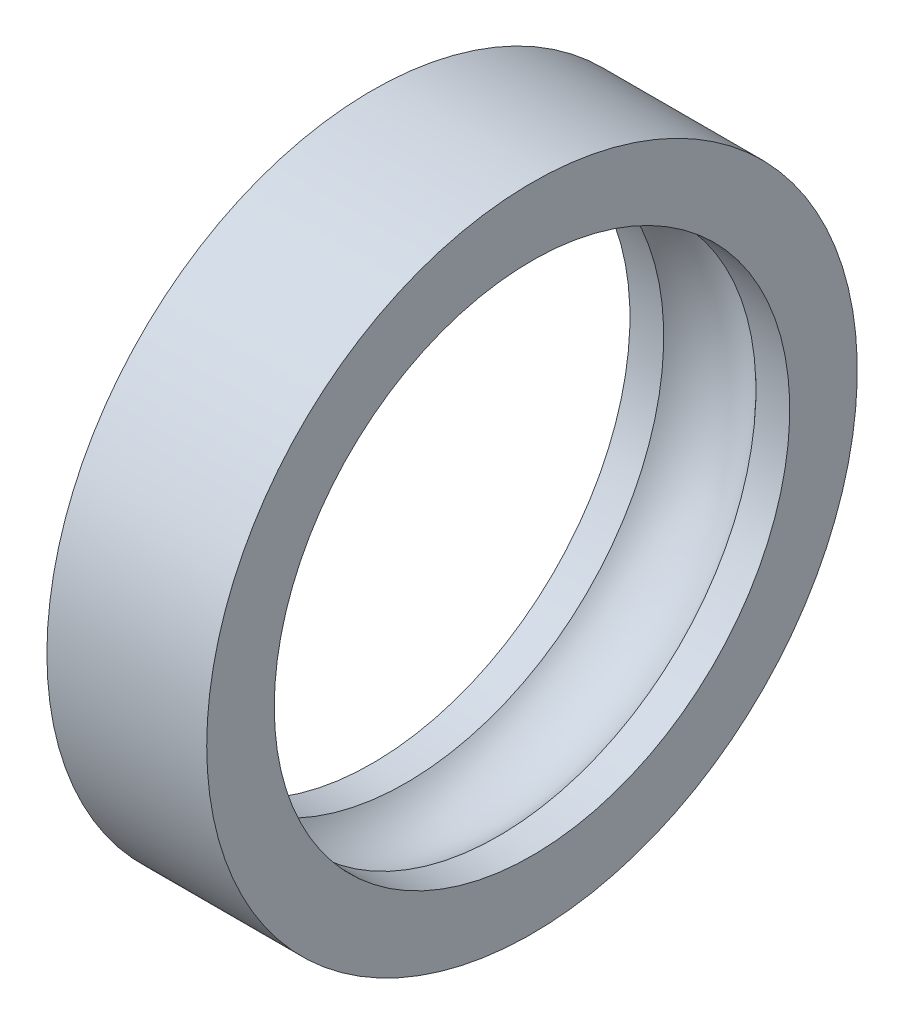
SolidWorks part; units mm, degrees
ref_plane "Front Plane" through (0, 0, 0) normal (0, 0, 1) x (1, 0, 0)
ref_plane "Top Plane" through (0, 0, 0) normal (0, 1, 0) x (1, 0, 0)
ref_plane "Right Plane" through (0, 0, 0) normal (1, 0, 0) x (0, 0, -1)
sketch "Sketch1" plane through (0, 0, 0) normal (0, 0, 1) x (1, 0, 0)
  line L0 (0, 56.5522) -> (0, -1.0828) construction
  line L1 (-33.6366, 0) -> (38.4304, 0) construction
  line L2 (-15.5, 63.1031) -> (15.5, 63.1031)
  line L3 (-15.5, 63.1031) -> (-15.5, 50)
  line L5 (15.5, 63.1031) -> (15.5, 50.0012)
  line L6 (-15.5, 63.1031) -> (15.5, 50.0012) construction
  line L7 (-15.5, 50) -> (15.5, 63.1031) construction
  line L8 (-15.5, 50) -> (-8.9443, 50)
  line L9 (8.9443, 50) -> (15.5, 50.0012)
  arc A0 (8.9443, 50) -> (-8.9443, 50) centre (0, 42) ccw
  point P0 (0.0007, 56.5519)
  dimension "D7" = 12
  dimension "D1" = 31
  dimension "D2" = 50
  dimension "D3" = 72.067
  dimension "D4" = 63.1031
  dimension "D6" = 57.635
  dimension "D8" = 33.655
revolve "Revolve3" add sketch "Sketch1" angle 360 about L1
